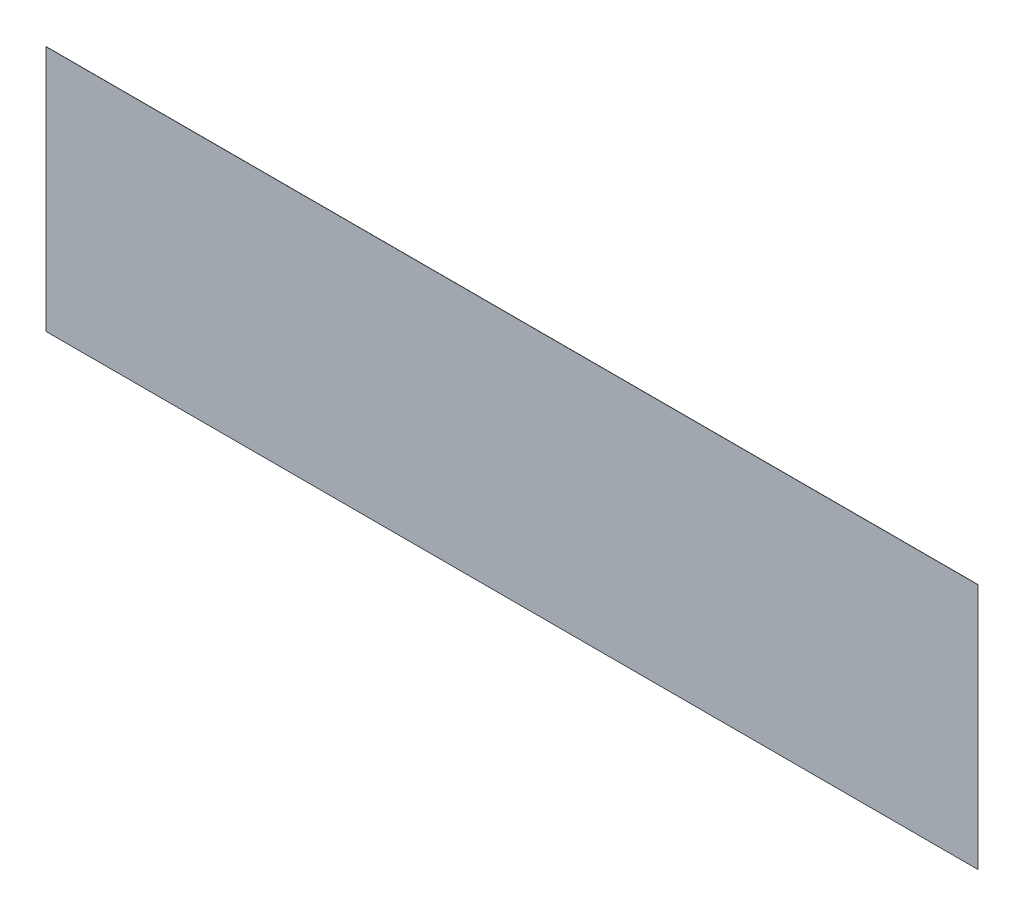
SolidWorks part; units mm, degrees
ref_plane "Front Plane" through (0, 0, 0) normal (0, 0, 1) x (1, 0, 0)
ref_plane "Top Plane" through (0, 0, 0) normal (0, 1, 0) x (1, 0, 0)
ref_plane "Right Plane" through (0, 0, 0) normal (1, 0, 0) x (0, 0, -1)
sketch "Sketch1" plane through (0, 0, 0) normal (0, 0, 1) x (1, 0, 0)
  line L1 (0, 0) -> (47916, 0)
  line L2 (0, 0) -> (0, 12681.5)
  line L3 (0, 12681.5) -> (47916, 12681.5)
  line L4 (47916, 0) -> (47916, 12681.5)
  dimension "D1" = 47916
  dimension "D2" = 12681.5
extrude "Boss-Extrude1" add sketch "Sketch1" against normal blind 10
